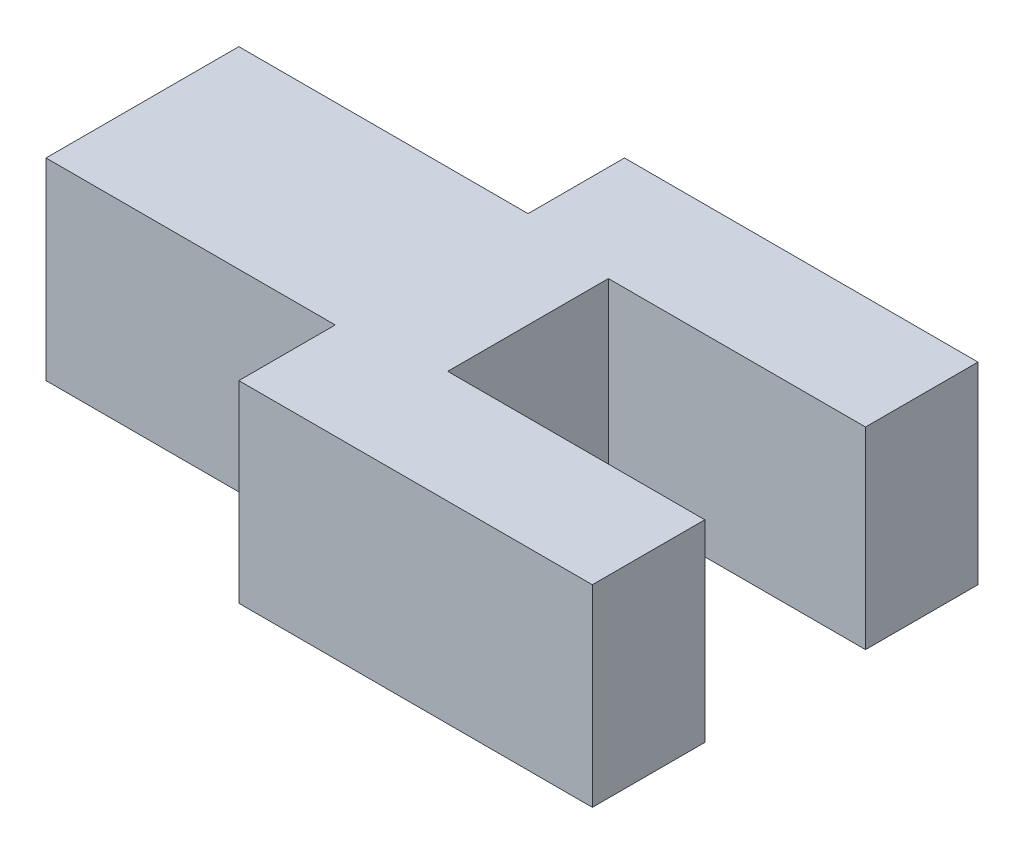
SolidWorks part; units mm, degrees
ref_plane "Front Plane" through (0, 0, 0) normal (0, 0, 1) x (1, 0, 0)
ref_plane "Top Plane" through (0, 0, 0) normal (0, 1, 0) x (1, 0, 0)
ref_plane "Right Plane" through (0, 0, 0) normal (1, 0, 0) x (0, 0, -1)
sketch "Sketch1" plane through (0, 0, 0) normal (0, 1, 0) x (1, 0, 0)
  line L0 (45, 12.5) -> (45, 30)
  line L1 (-10, -30) -> (45, -30)
  line L2 (-55, -15) -> (-55, 15)
  line L3 (-10, 30) -> (45, 30)
  line L4 (45, -30) -> (45, -12.5)
  line L7 (45, -12.5) -> (5, -12.5)
  line L9 (45, 12.5) -> (5, 12.5)
  line L10 (5, -12.5) -> (5, 12.5)
  line L15 (-55, -15) -> (-10, -15)
  line L16 (-10, -30) -> (-10, -15)
  line L19 (-55, 15) -> (-10, 15)
  line L20 (-10, 30) -> (-10, 15)
  point P0 (0, 0)
  point P5 (50, 0)
extrude "Boss-Extrude1" add sketch "Sketch1" along normal blind 30
